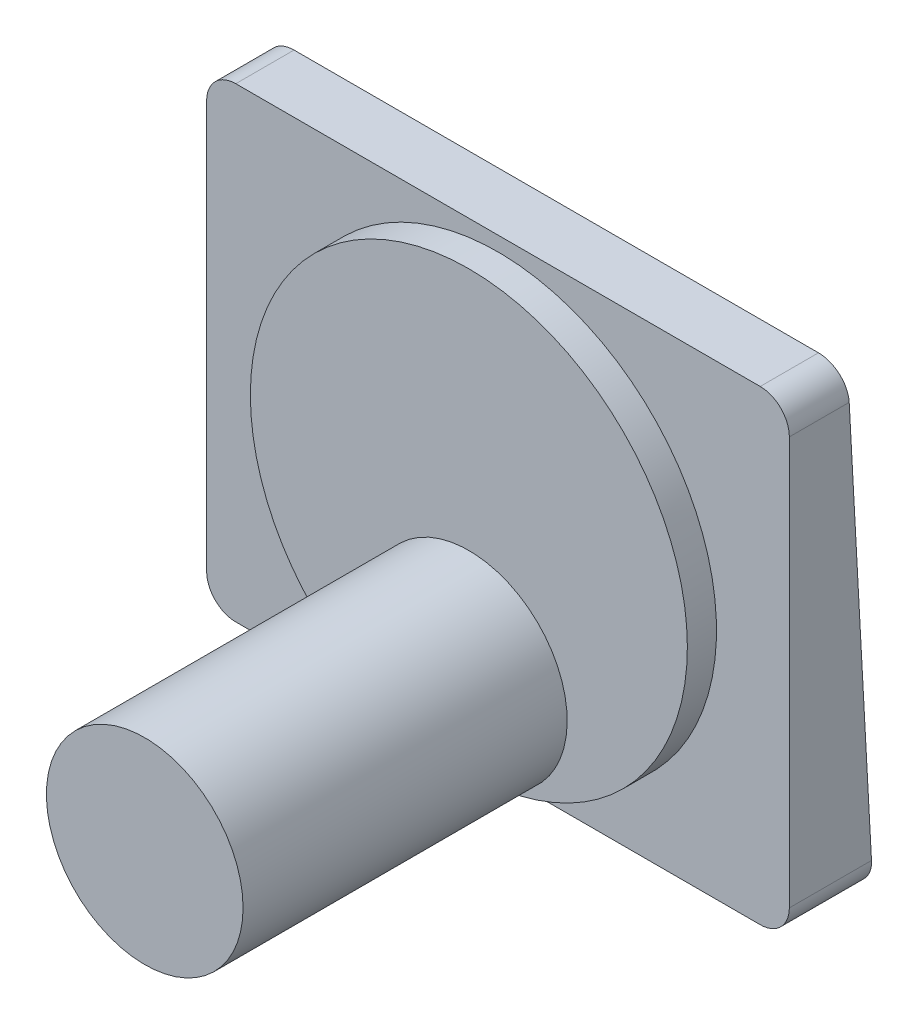
SolidWorks part; units mm, degrees
ref_plane "Front Plane" through (0, 0, 0) normal (0, 0, 1) x (1, 0, 0)
ref_plane "Top Plane" through (0, 0, 0) normal (0, 1, 0) x (1, 0, 0)
ref_plane "Right Plane" through (0, 0, 0) normal (1, 0, 0) x (0, 0, -1)
sketch "Sketch1" plane through (0, 0, 0) normal (1, 0, 0) x (0, 0, -1)
  line L0 (0, 32) -> (0, -32)
  line L1 (0, -32) -> (11.5, -32)
  line L2 (11.5, -32) -> (8, 32)
  line L3 (8, 32) -> (0, 32)
  dimension "D1" = 11.5
  dimension "D2" = 8
  dimension "D3" = 64
extrude "Boss-Extrude1" add sketch "Sketch1" along normal mid plane 80
fillet "Fillet1" radius 4 4 edges at (-40, -32, -5.75) (40, -32, -5.75) (-40, 32, -4) (40, 32, -4)
sketch "Sketch2" plane through (0, 0, 0) normal (0, 0, 1) x (1, 0, 0)
  circle A0 centre (0, 0) radius 30
  dimension "D1" = 60
extrude "Boss-Extrude2" add sketch "Sketch2" along normal blind 4
sketch "Sketch3" plane through (0, 0, 4) normal (0, 0, 1) x (1, 0, 0)
  circle A0 centre (0, -17) radius 13.5
  point P2 (0, 0)
  dimension "D1" = 27
  dimension "D2" = 17
extrude "Boss-Extrude3" add sketch "Sketch3" along normal blind 44.5
equation "\"D1@Boss-Extrude3\"=37+11.5-4"
